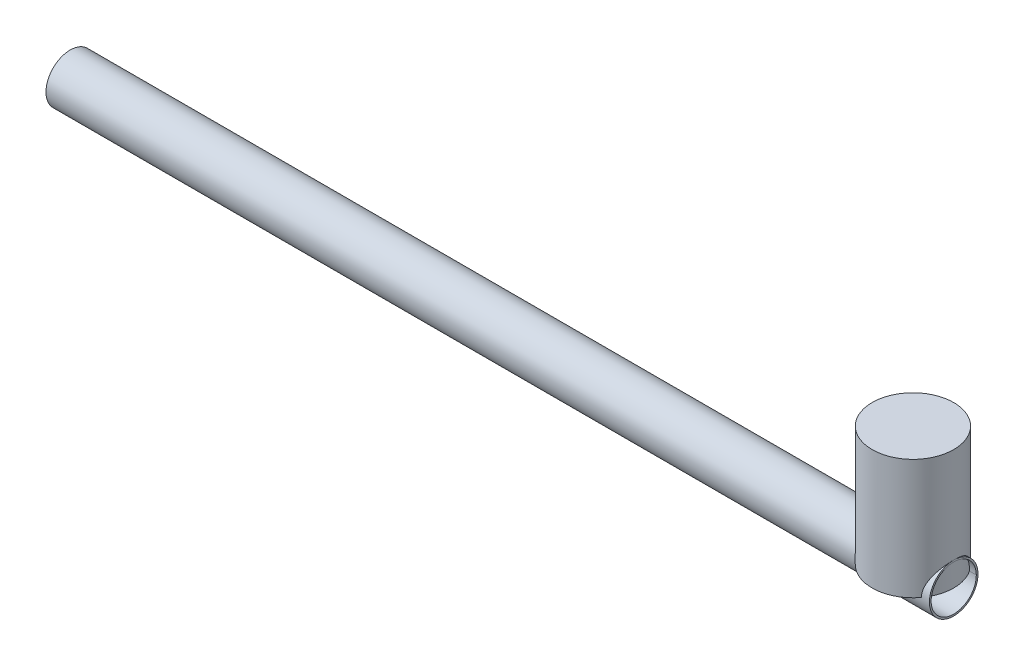
SolidWorks part; units mm, degrees
ref_plane "Front Plane" through (0, 0, 0) normal (0, 0, 1) x (1, 0, 0)
ref_plane "Top Plane" through (0, 0, 0) normal (0, 1, 0) x (1, 0, 0)
ref_plane "Right Plane" through (0, 0, 0) normal (1, 0, 0) x (0, 0, -1)
sketch "Sketch1" plane through (0, 0, 0) normal (1, 0, 0) x (0, 0, -1)
  circle A0 centre (0, 0) radius 12.7
  circle A1 centre (0, 0) radius 11.811
extrude "Boss-Extrude1" add sketch "Sketch1" along normal blind 461.982
sketch "Sketch2" plane through (0, 0, 0) normal (0, 1, 0) x (1, 0, 0)
  circle A0 centre (440.6507, 0) radius 21.3313
extrude "Boss-Extrude2" add sketch "Sketch2" along normal blind 62.7
